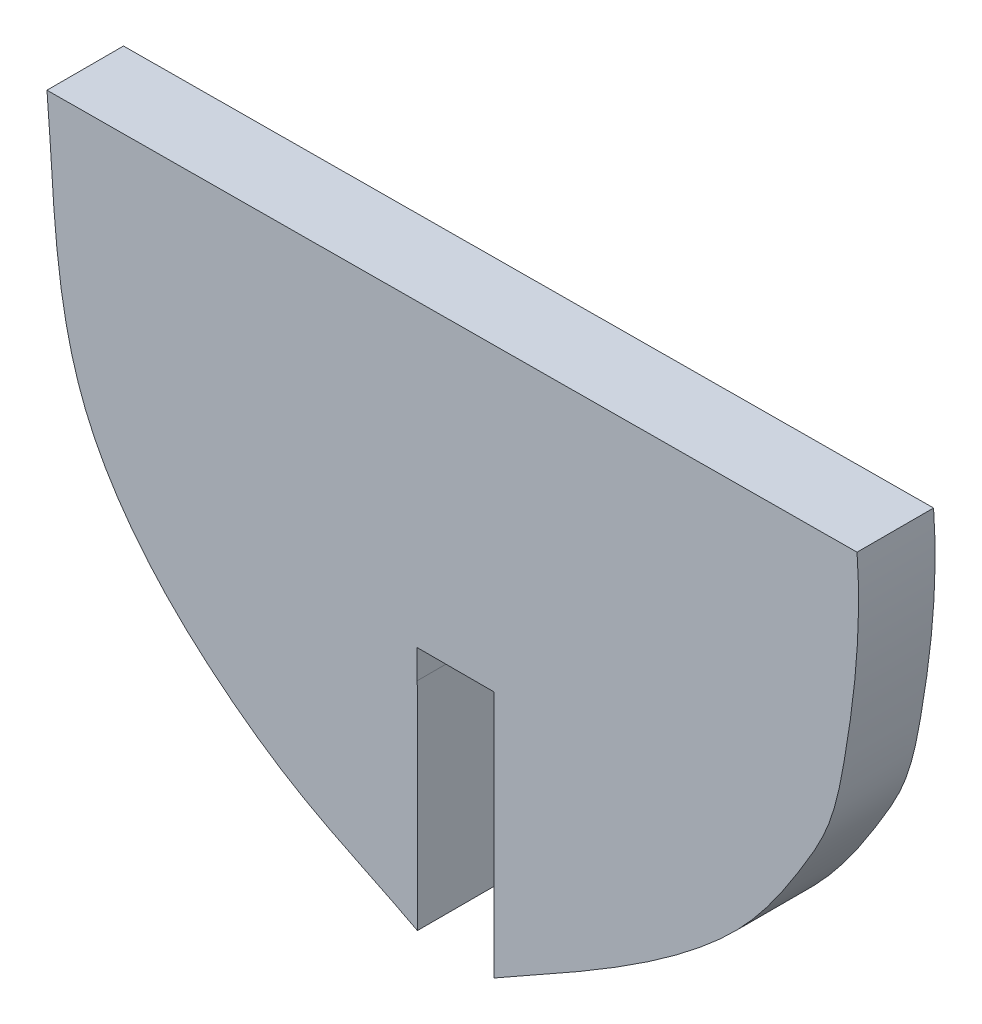
SolidWorks part; units mm, degrees
ref_plane "前视基准面" through (0, 0, 0) normal (0, 0, 1) x (1, 0, 0)
ref_plane "上视基准面" through (0, 0, 0) normal (0, 1, 0) x (1, 0, 0)
ref_plane "右视基准面" through (0, 0, 0) normal (1, 0, 0) x (0, 0, -1)
other "Configuration Table"
sketch "草图1" plane through (0, 0, 0) normal (0, 0, 1) x (1, 0, 0)
  line L0 (376.5, 617) -> (1882.5, 617) construction
  line L1 (9.8841, 48.891) -> (9.8626, 71.7972)
  line L3 (1.8593, 71.7896) -> (1.8806, 49.182)
  line L4 (47.8337, 106.4158) -> (-36.8476, 105.899)
  line L5 (1.8593, 71.7896) -> (1.8593, 74.7896)
  line L6 (9.8626, 71.7972) -> (9.8626, 74.7896)
  line L7 (9.8626, 74.7896) -> (1.8593, 74.7896)
  spline S0 degree 3 poles (47.8337, 106.4158) (48.3195, 99.869) (47.3705, 91.0399) (45.2673, 80.3525) (41.4971, 73.9278) (37.0878, 67.3102) (26.4864, 57.9326) (16.7974, 52.7994) (9.8841, 48.891) knots 0 0 0 0 0.26257 0.359675 0.434109 0.560787 0.678988 1 1 1 1
  spline S1 degree 3 poles (1.8806, 49.182) (-2.1475, 51.3201) (-9.3686, 54.4059) (-18.6845, 60.9207) (-26.7565, 68.3679) (-36.3372, 82.7405) (-36.0665, 97.0428) (-36.8476, 105.899) knots 0 0 0 0 0.184933 0.316628 0.458401 0.629057 1 1 1 1
  dimension "D1" = 8.0033
  dimension "D2" = 25.8987
extrude "凸台-拉伸1" add sketch "草图1" along normal blind 8
